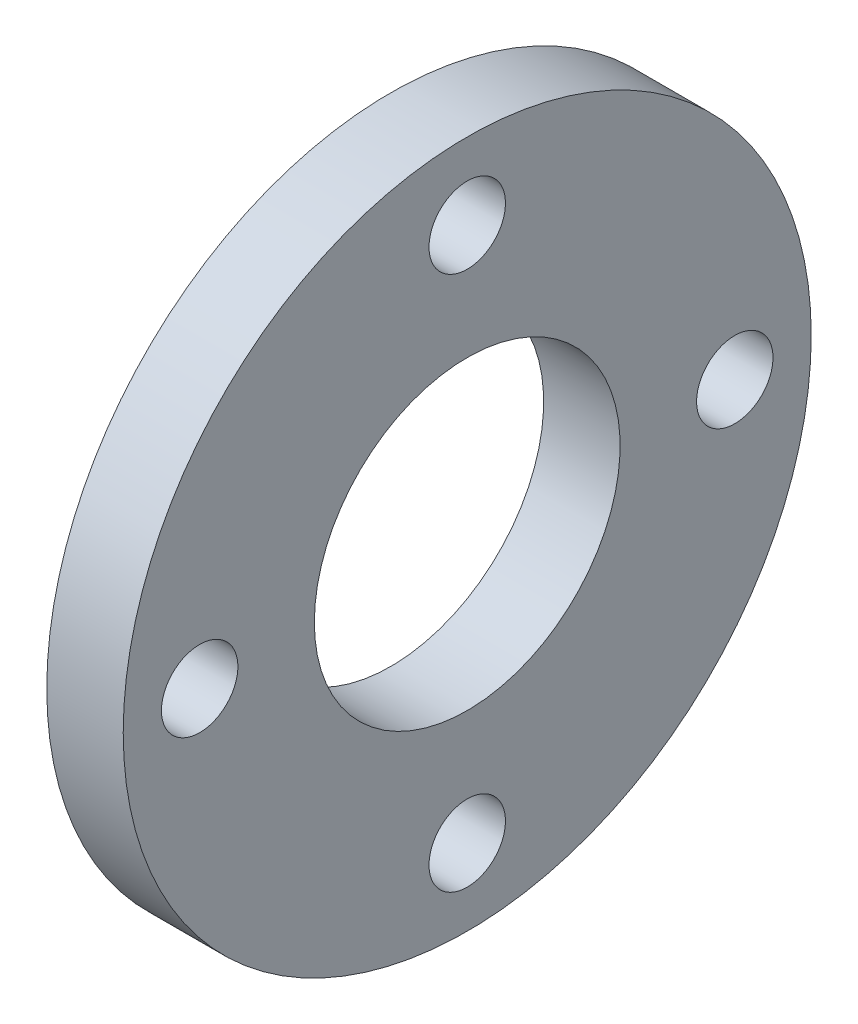
SolidWorks part; units mm, degrees
ref_plane "Front Plane" through (0, 0, 0) normal (0, 0, 1) x (1, 0, 0)
ref_plane "Top Plane" through (0, 0, 0) normal (0, 1, 0) x (1, 0, 0)
ref_plane "Right Plane" through (0, 0, 0) normal (1, 0, 0) x (0, 0, -1)
sketch "Sketch1" plane through (33.3375, 0, 0) normal (-1, 0, 0) x (0, 0, 1)
  line L0 (-3.2066, 186.9315) -> (19.0184, 186.9315) construction
  circle A0 centre (-3.2066, 186.9315) radius 12.7 construction
  circle A1 centre (-3.2066, 186.9315) radius 12.7
  circle A2 centre (19.0184, 186.9315) radius 3.175
  circle A3 centre (-3.2066, 164.7065) radius 3.175
  circle A4 centre (-25.4316, 186.9315) radius 3.175
  circle A5 centre (-3.2066, 209.1565) radius 3.175
  circle A6 centre (-3.2066, 186.9315) radius 28.575
  point P14 (-3.2066, 186.9315)
  dimension "D3" = 6.35
  dimension "D4" = 57.15
  dimension "D1" = 22.225
  dimension "D2" = 4
extrude "Boss-Extrude1" add sketch "Sketch1" along normal blind 6.35
